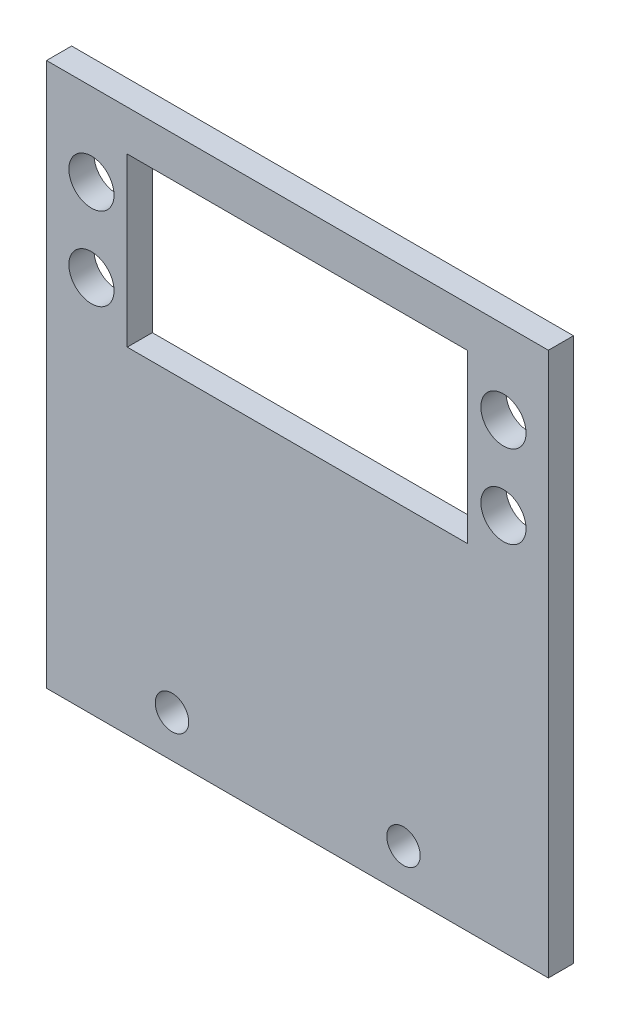
SolidWorks part; units mm, degrees
ref_plane "Front Plane" through (0, 0, 0) normal (0, 0, 1) x (1, 0, 0)
ref_plane "Top Plane" through (0, 0, 0) normal (0, 1, 0) x (1, 0, 0)
ref_plane "Right Plane" through (0, 0, 0) normal (1, 0, 0) x (0, 0, -1)
sketch "Sketch1" plane through (0, 0, 0) normal (0, 0, 1) x (1, 0, 0)
  line L5 (0, 0) -> (60, 0)
  line L6 (0, 0) -> (0, 65)
  line L7 (0, 65) -> (60, 65)
  line L8 (60, 0) -> (60, 65)
  line L10 (50.35, 40.1453) -> (9.65, 40.1453)
  line L11 (50.35, 40.1453) -> (50.35, 60.1453)
  line L12 (50.35, 60.1453) -> (9.65, 60.1453)
  line L13 (9.65, 40.1453) -> (9.65, 60.1453)
  circle A0 centre (5.3706, 55.0953) radius 2.7
  circle A1 centre (5.3706, 45.1953) radius 2.7
  circle A2 centre (54.63, 55.0953) radius 2.7
  circle A3 centre (54.63, 45.1953) radius 2.7
  circle A4 centre (15, 5) radius 2
  circle A5 centre (42.6772, 5) radius 2
  point P5 (0, 0)
  dimension "D1" = 9.65
  dimension "D4" = 4.2794
  dimension "D2" = 9.65
  dimension "D3" = 40.7
  dimension "D5" = 4.28
  dimension "D6" = 4.28
  dimension "D7" = 15
  dimension "D8" = 17.3228
  dimension "D9" = 27.6772
extrude "Boss-Extrude1" add sketch "Sketch1" along normal blind 3
